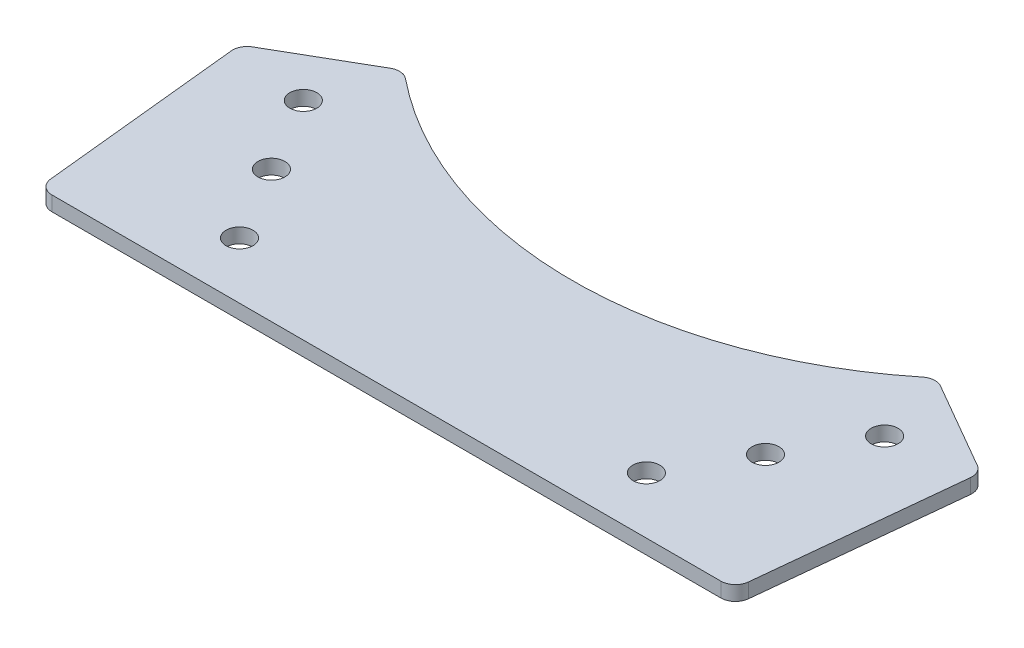
SolidWorks part; units mm, degrees
material "FR4_stuffedProtoboard"
ref_plane "Front Plane" through (0, 0, 0) normal (0, 0, 1) x (1, 0, 0)
ref_plane "Top Plane" through (0, 0, 0) normal (0, 1, 0) x (1, 0, 0)
ref_plane "Right Plane" through (0, 0, 0) normal (1, 0, 0) x (0, 0, -1)
sketch "Sketch1" plane through (0, 0, 0) normal (0, 1, 0) x (1, 0, 0)
  line L0 (-38.1, 9.525) -> (38.1, -9.525) construction
  line L1 (-38.1, 9.525) -> (38.1, 9.525)
  line L2 (-38.1, 9.525) -> (-38.1, -9.525)
  line L3 (-38.1, -9.525) -> (38.1, -9.525)
  line L4 (38.1, 9.525) -> (38.1, -9.525)
  point P4 (0, 0)
  dimension "D1" = 19.05
  dimension "D2" = 76.2
extrude "Boss-Extrude1" add sketch "Sketch1" along normal blind 1.6
sketch "Sketch2" plane through (0, 0, 0) normal (0, -1, 0) x (1, 0, 0)
  line L0 (0, 43.3118) -> (-53.8944, -50.0361) construction
  line L1 (0, -0.88) -> (0, 0.88) construction
  line L2 (-38.1, 9.525) -> (38.1, 9.525) construction
  line L3 (-40.4812, -13.6494) -> (-29.0892, -20.2266)
  line L4 (-29.0892, -20.2266) -> (-22.9106, -9.525)
  line L5 (-22.9106, -9.525) -> (-34.3027, -2.9478)
  line L6 (-34.3027, -2.9478) -> (-40.4812, -13.6494)
  line L7 (38.1, -9.525) -> (-38.1, -9.525) construction
  point P2 (-34.7852, -16.938)
  point P5 (-49.537, -6.5559)
  point P6 (-23.3449, -7.1863)
  point P9 (-31.269, -22.5887)
  point P12 (0, 0)
  dimension "D1" = 33.7868
  dimension "D2" = 30
  dimension "D3" = 4.7625
extrude "Boss-Extrude2" add sketch "Sketch2" against normal up to surface (1.6 mm away) up to face at (0, 1.6, 0)
sketch "Sketch3" plane through (0, 0, 0) normal (0, -1, 0) x (1, 0, 0)
  line L0 (-38.1, 9.525) -> (-40.4812, -13.6494)
  line L1 (-40.4812, -13.6494) -> (-22.9106, -9.525)
  line L2 (-22.9106, -9.525) -> (-38.1, 9.525)
extrude "Boss-Extrude3" add sketch "Sketch3" against normal up to surface (1.6 mm away) up to face at (-13.2116, 1.6, -6.2002)
mirror "Mirror1" about plane through (0, 0, 0) normal (1, 0, 0) of "Boss-Extrude3", "Boss-Extrude2"
sketch "Sketch4" plane through (0, 0, 0) normal (0, -1, 0) x (1, 0, 0)
  line L0 (-29.0892, -20.2266) -> (-29.0892, 9.525)
  line L1 (-38.1, 9.525) -> (38.1, 9.525) construction
  line L2 (-29.0892, 9.525) -> (29.0892, 9.525)
  line L3 (29.0892, 9.525) -> (29.0892, -20.2266)
  arc A0 (-29.0892, -20.2266) -> (29.0892, -20.2266) centre (0, -54.4111) cw
extrude "Boss-Extrude4" add sketch "Sketch4" against normal up to surface (1.6 mm away) up to face at (0, 1.6, -8.469)
sketch "Sketch5" plane through (0, 0, 0) normal (0, -1, 0) x (1, 0, 0)
  line L0 (-38.1, 9.525) -> (-37.9695, 10.795)
  line L1 (-37.9695, 10.795) -> (37.9695, 10.795)
  line L2 (37.9695, 10.795) -> (38.1, 9.525)
  line L3 (-38.1, 9.525) -> (-40.4812, -13.6494) construction
  line L4 (38.1, 9.525) -> (40.4812, -13.6494) construction
  line L5 (-38.1, 9.525) -> (38.1, 9.525) construction
  line L6 (-38.1, 9.525) -> (38.1, 9.525)
  dimension "D1" = 1.27
extrude "Boss-Extrude5" add sketch "Sketch5" against normal up to surface (1.6 mm away) up to face at (0, 1.6, -6.3334)
fillet "Fillet4" radius 1.5875 6 edges at (40.4812, 0.8, -13.6494) (37.9695, 0.8, 10.795) (-40.4812, 0.8, -13.6494) (-29.0892, 0.8, -20.2266) (29.0892, 0.8, -20.2266) (-37.9695, 0.8, 10.795)
sketch "Sketch6" plane through (0, 0, 0) normal (0, -1, 0) x (1, 0, 0)
  line L0 (0, -0.88) -> (0, 0.88) construction
  line L1 (36.5368, 10.795) -> (-36.5368, 10.795) construction
  point P0 (0, 0)
  point P4 (0, 0)
  point P5 (0, 0)
  point P6 (0, 0)
  point P10 (-22.225, 4.6217)
  point P11 (-26.9875, -3.6272)
  point P12 (-31.75, -11.8761)
  point P15 (0, 0)
  dimension "D1" = 22.225
  dimension "D2" = 26.9875
  dimension "D3" = 31.75
  dimension "D4" = 6.1733
  dimension "D5" = 14.4222
  dimension "D6" = 22.6711
hole_wizard "#4 Clearance Hole1" positions "3DSketch1" profile "Sketch7" hole size "#4" standard "ANSI Inch" end condition through all
sketch3d "3DSketch1"
  point P0 (-22.225, 0, 4.6217)
  point P3 (-26.9875, 0, -3.6272)
  point P6 (-31.75, 0, -11.8761)
  point P9 (0, 0, 0)
sketch "Sketch7" plane through (-22.225, 0, 4.6217) normal (1, 0, 0) x (0, 0, -1)
  line L0 (0, 0) -> (0, 1.6)
  line L1 (0, 1.6) -> (1.4732, 1.6)
  line L2 (1.4732, 1.6) -> (1.4732, 0)
  line L5 (1.4732, 0) -> (0, 0)
  line L11 (0, -6.35) -> (0, 107.95) construction
  dimension "Thru Hole Dia." = 2.9464
  dimension "Thru Hole Depth" = 1.6
mirror "Mirror2" about plane through (0, 0, 0) normal (1, 0, 0) of "#4 Clearance Hole1"
